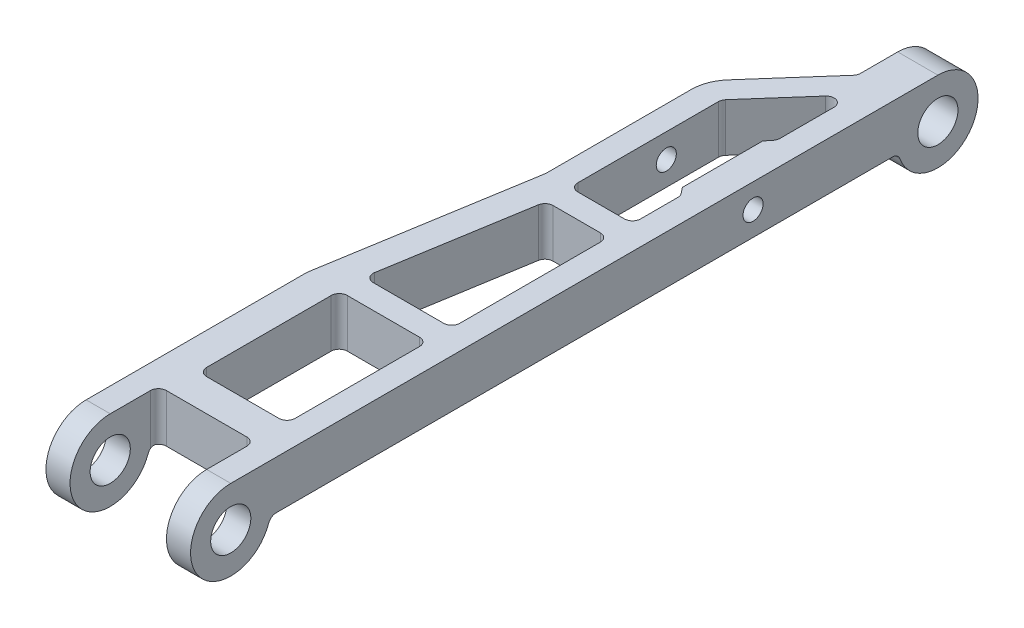
SolidWorks part; units mm, degrees
material "6061 合金"
ref_plane "前视基准面" through (0, 0, 0) normal (0, 0, 1) x (1, 0, 0)
ref_plane "上视基准面" through (0, 0, 0) normal (0, 1, 0) x (1, 0, 0)
ref_plane "右视基准面" through (0, 0, 0) normal (1, 0, 0) x (0, 0, -1)
sketch "草图1" plane through (0, 0, 0) normal (0, 1, 0) x (1, 0, 0)
  line L0 (-22.5, 87) -> (-27.5, 87)
  line L1 (-27.5, 87) -> (-27.5, 77)
  line L2 (-27.5, 77) -> (-36.3, 67)
  line L3 (-40.5, 21.5) -> (-40.5, -11)
  line L4 (-40.5, -11) -> (-37.5, -11)
  line L5 (-37.5, -11) -> (-37.5, 0)
  line L6 (-37.5, 0) -> (-25.5, 0)
  line L7 (-22.5, 87) -> (-22.5, -11)
  line L17 (-22.5, 82) -> (-27.5, 82) construction
  line L18 (-37.5, -6) -> (-40.5, -6) construction
  line L20 (-36.3, 67) -> (-36.3, 47)
  line L21 (-26.3, 64) -> (-33.3, 64)
  line L22 (-26.3, 64) -> (-26.3, 54)
  line L23 (-26.3, 54) -> (-33.3, 54)
  line L24 (-33.3, 64) -> (-33.3, 54)
  line L25 (-36.3, 47) -> (-40.5, 21.5)
  line L26 (-25.5, 0) -> (-25.5, -11)
  line L27 (-25.5, -11) -> (-22.5, -11)
  line L28 (-33.3, 59) -> (-26.3, 59) construction
  dimension "D2" = 5
  dimension "D3" = 7
  dimension "D4" = 88
  dimension "D5" = 5
  dimension "D6" = 5
  dimension "D7" = 11
  dimension "D8" = 10
  dimension "D9" = 23
  dimension "D10" = 3
  dimension "D11" = 3
  dimension "D12" = 12
  dimension "D13" = 20
  dimension "D14" = 32.5
  dimension "D15" = 22.5
  dimension "D16" = 3
  dimension "D17" = 3.8
extrude "凸台-拉伸1" add sketch "草图1" along normal mid plane 10
sketch "草图5" plane through (0, 5, 0) normal (0, 1, 0) x (1, 0, 0)
  line L0 (-25.5, 72.0815) -> (-25.5, 65)
  line L1 (-26.3, 64) -> (-33.3, 64)
  line L2 (-33.3, 65.868) -> (-27.2507, 72.7421)
  line L3 (-25.5, 53) -> (-25.5, 47)
  line L4 (-25.5, 4) -> (-36.5, 4)
  line L5 (-36.5, 4) -> (-36.5, 21.5)
  line L6 (-36.4587, 24.5) -> (-33.247, 44)
  line L7 (-33.3, 47) -> (-33.3, 54)
  line L8 (-37.5, 0) -> (-25.5, 0) construction
  line L9 (-40.5, 21.5) -> (-40.5, -11) construction
  line L10 (-36.3, 47) -> (-40.5, 21.5) construction
  line L11 (-33.3, 54) -> (-26.3, 54)
  line L12 (-27.5, 77) -> (-36.3, 67) construction
  line L13 (-33.3, 65.868) -> (-33.3, 64)
  line L15 (-33.3, 47) -> (-25.5, 47)
  line L16 (-33.247, 44) -> (-25.5, 44)
  line L17 (-36.4587, 24.5) -> (-25.5, 24.5)
  line L18 (-36.5, 21.5) -> (-25.5, 21.5)
  line L19 (-25.5, 44) -> (-25.5, 24.5)
  line L20 (-25.5, 21.5) -> (-25.5, 4)
  line L21 (-22.5, -11) -> (-22.5, 87) construction
  line L23 (-26.3, 64) -> (-25.5, 65)
  line L24 (-26.3, 54) -> (-25.5, 53)
  arc A0 (-25.5, 72.0815) -> (-27.2507, 72.7421) centre (-26.5, 72.0815) ccw
  dimension "D10" = 1
  dimension "D1" = 4
  dimension "D2" = 4
  dimension "D3" = 3.5
  dimension "D5" = 3
  dimension "D7" = 3
  dimension "D8" = 3
  dimension "D9" = 3
  dimension "D11" = 1
  dimension "D12" = 1
extrude "切除-拉伸3" cut sketch "草图5" against normal through all
hole_wizard "M3 螺纹孔1" positions "草图3" profile "草图4" tap size "M3" standard "GB" end condition through all
sketch "草图3" plane through (-36.3, 0, 0) normal (-1, 0, 0) x (0, 0, 1)
  line L0 (-67, 0) -> (-47, 0) construction
  point P4 (-59, 2)
  dimension "D1" = 2
sketch "草图4" plane through (-36.3, 2, -59) normal (0, 1, 0) x (0, 0, 1)
  line L0 (0, 0) -> (0, 13.8)
  line L1 (0, 13.8) -> (1.25, 13.8)
  line L2 (1.25, 13.8) -> (1.25, 0)
  line L5 (1.25, 0) -> (0, 0)
  line L11 (0, -6.35) -> (0, 107.95) construction
  dimension "通孔螺纹孔钻头直径" = 2.5
  dimension "通孔螺纹孔钻头深度" = 13.8
cosmetic thread "孔螺蚊线1" parameters "D2"=3
sketch "草图2" plane through (0, 0, 0) normal (1, 0, 0) x (0, 0, -1)
  line L0 (-11, 5) -> (-11, -5) construction
  line L1 (87, 5) -> (87, -5) construction
  line L2 (82, 5) -> (88, 5)
  line L3 (88, 5) -> (88, -6)
  line L4 (88, -6) -> (-12, -6)
  line L5 (-6, 5) -> (-12, 5)
  line L6 (-12, 5) -> (-12, -6)
  line L8 (76.3431, -1) -> (-0.3431, -1)
  line L9 (67, 5) -> (47, 5) construction
  line L11 (87, -5) -> (77, -5) construction
  circle A0 centre (-6, 0) radius 2.5
  circle A1 centre (82, 0) radius 2.5
  arc A2 (77.286, -1.6667) -> (82, 5) centre (82, 0) ccw
  arc A3 (-6, 5) -> (-1.286, -1.6667) centre (-6, 0) ccw
  arc A5 (-1.286, -1.6667) -> (-0.3431, -1) centre (-0.3431, -2) cw
  arc A6 (77.286, -1.6667) -> (76.3431, -1) centre (76.3431, -2) ccw
  dimension "D1" = 5
  dimension "D2" = 1
  dimension "D4" = 6
  dimension "D5" = 1
  dimension "D3" = 1
  dimension "D6" = 1
extrude "切除-拉伸1" cut sketch "草图2" against normal through all both and the other way through all
fillet "圆角1" radius 1 16 edges at (-37.5, 2, 0) (-36.5, 2, -21.5) (-36.5, 2, -4) (-25.5, 2, -4) (-25.5, 2, -21.5) (-25.5, 2, -24.5) (-36.4587, 2, -24.5) (-33.247, 2, -44) (-25.5, 2, -44) (-33.3, 2, -65.868) (-33.3, 2, -47) (-25.5, 2, -47) (-25.5, 2, -53) (-25.5, 2, -65) (-27.5, 1.877, -77) (-25.5, 2, 0)
fillet "圆角2" radius 5 3 edges at (-36.3, 2, -67) (-40.5, 2, -21.5) (-36.3, 2, -47)
